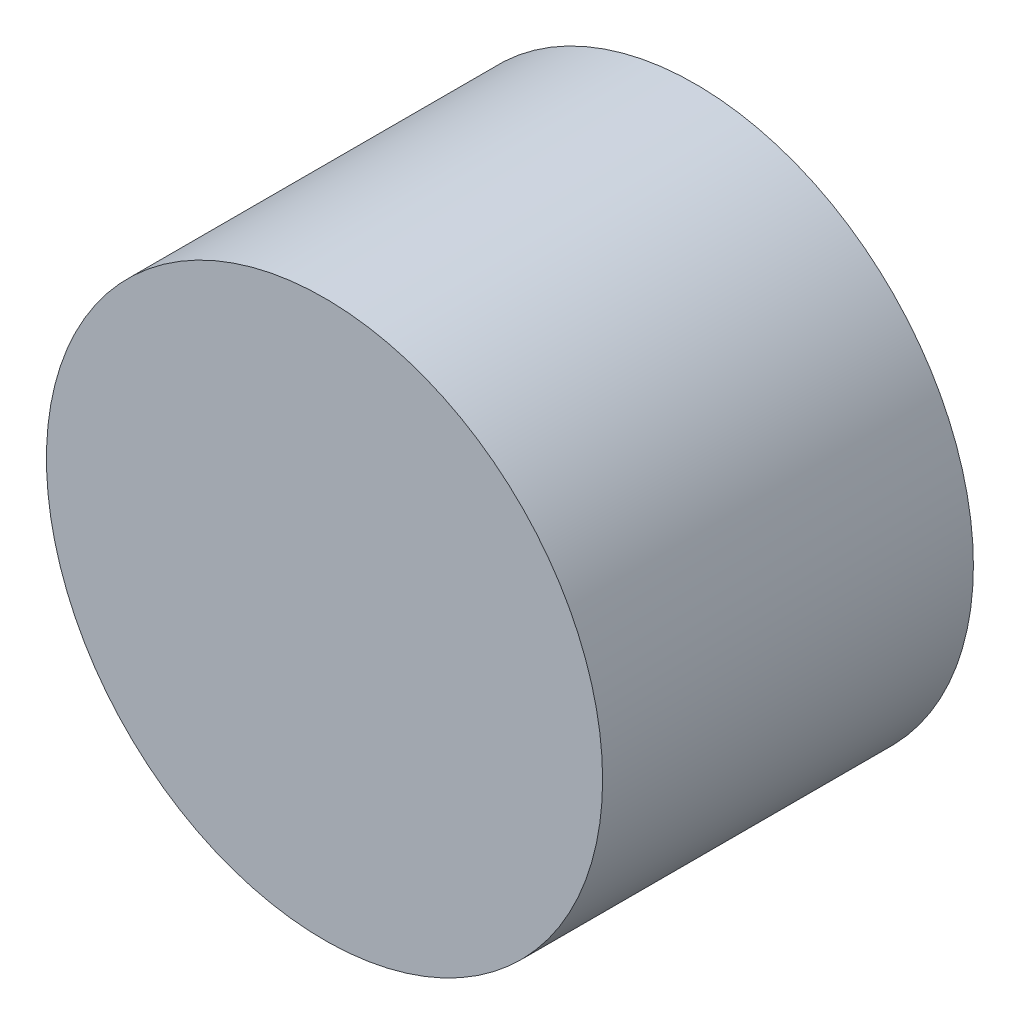
SolidWorks part; units mm, degrees
ref_plane "前视基准面" through (0, 0, 0) normal (0, 0, 1) x (1, 0, 0)
ref_plane "上视基准面" through (0, 0, 0) normal (0, 1, 0) x (1, 0, 0)
ref_plane "右视基准面" through (0, 0, 0) normal (1, 0, 0) x (0, 0, -1)
sketch "草图1" plane through (0, 0, 0) normal (0, 0, 1) x (1, 0, 0)
  circle A0 centre (0, 0) radius 3.75
  dimension "D1" = 7.5
extrude "凸台-拉伸1" add sketch "草图1" along normal blind 5
